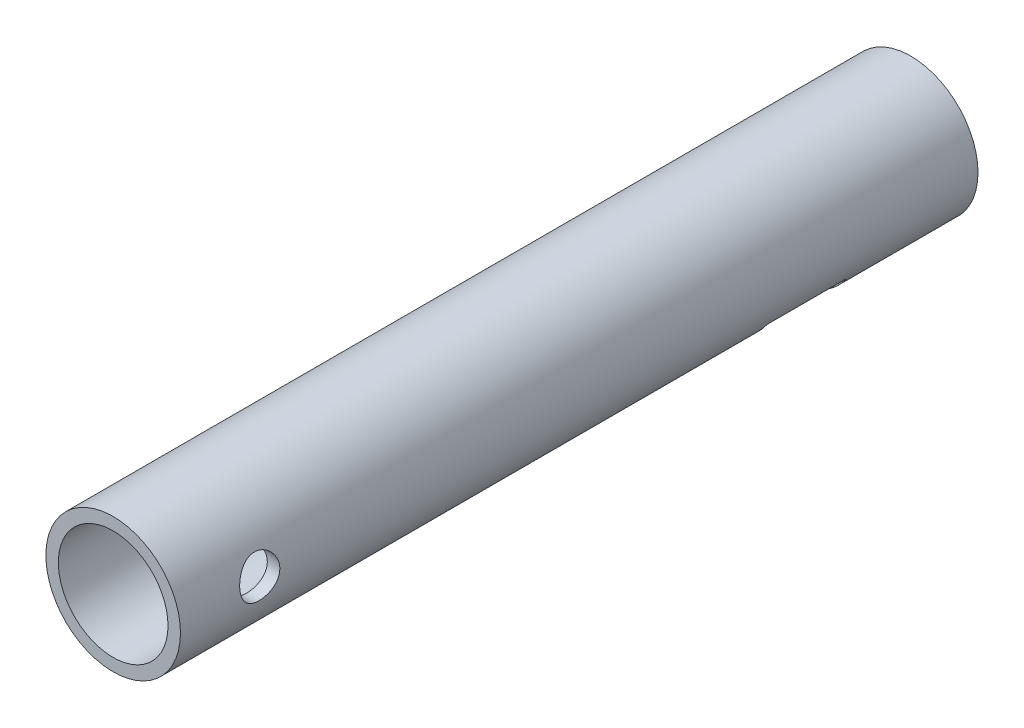
SolidWorks part; units mm, degrees
ref_plane "Front Plane" through (0, 0, 0) normal (0, 0, 1) x (1, 0, 0)
ref_plane "Top Plane" through (0, 0, 0) normal (0, 1, 0) x (1, 0, 0)
ref_plane "Right Plane" through (0, 0, 0) normal (1, 0, 0) x (0, 0, -1)
sketch "Sketch1" plane through (0, 0, 0) normal (0, 0, 1) x (1, 0, 0)
  circle A0 centre (0, 0) radius 8.7312
  circle A1 centre (0, 0) radius 10.7156
  dimension "D1" = 17.4625
  dimension "D2" = 21.4312
extrude "Boss-Extrude1" add sketch "Sketch1" along normal blind 127
sketch "Sketch2" plane through (0, 0, 0) normal (0, 1, 0) x (1, 0, 0)
  line L1 (-8.89, -19.05) -> (8.89, -19.05)
  line L2 (-8.89, -19.05) -> (-8.89, -31.75)
  line L3 (-8.89, -31.75) -> (8.89, -31.75)
  line L4 (8.89, -19.05) -> (8.89, -31.75)
  line L5 (-8.89, -19.05) -> (8.89, -31.75) construction
  line L6 (-8.89, -31.75) -> (8.89, -19.05) construction
  line L7 (-10.7156, -127) -> (10.7156, -127) construction
  point P0 (0, -25.4)
  dimension "D1" = 12.7
  dimension "D2" = 101.6
  dimension "D3" = 17.78
extrude "Cut-Extrude1" cut sketch "Sketch2" against normal through all
sketch "Sketch5" plane through (0, 0, 0) normal (1, 0, 0) x (0, 0, -1)
  line L0 (0, 10.7156) -> (-127, 10.7156) construction
  line L1 (-127, 10.7156) -> (-127, -10.7156) construction
  circle A0 centre (-114.3, 1.1906) radius 3.175
  dimension "D1" = 6.35
  dimension "D2" = 9.525
  dimension "D3" = 12.7
extrude "Cut-Extrude2" cut sketch "Sketch5" against normal through all and the other way through all
